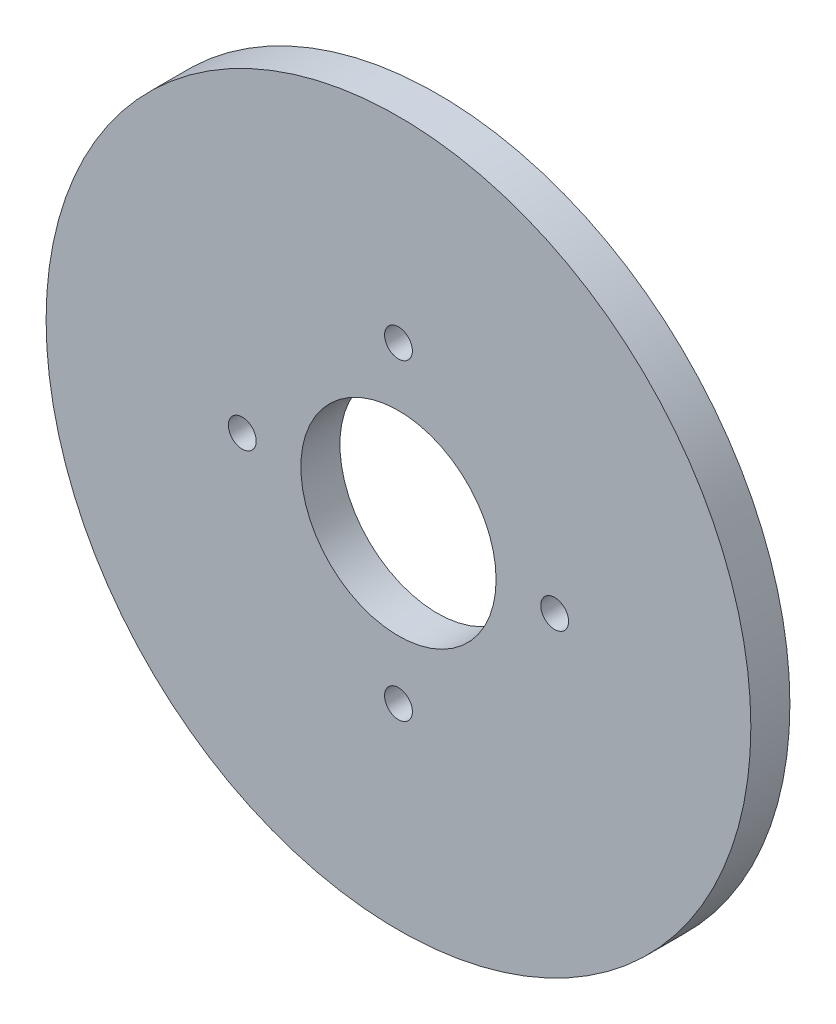
SolidWorks part; units mm, degrees
material "6061 Alloy"
ref_plane "Front Plane" through (0, 0, 0) normal (0, 0, 1) x (1, 0, 0)
ref_plane "Top Plane" through (0, 0, 0) normal (0, 1, 0) x (1, 0, 0)
ref_plane "Right Plane" through (0, 0, 0) normal (1, 0, 0) x (0, 0, -1)
sketch "Sketch1" plane through (0, 0, 0) normal (0, 0, 1) x (1, 0, 0)
  circle A0 centre (0, 0) radius 28.6512
  circle A1 centre (0, 0) radius 7.9375
  dimension "D1" = 57.3024
  dimension "D2" = 15.875
extrude "Boss-Extrude1" add sketch "Sketch1" along normal blind 3.175
hole_wizard "Tap Drill for #4-40 Tap1" positions "Sketch2" profile "Sketch3" hole size "#4-40" standard "ANSI Inch"
sketch "Sketch2" plane through (0, 0, 3.175) normal (0, 0, 1) x (1, 0, 0)
  point P0 (0, 12.7)
  point P2 (0, -12.7)
  point P4 (12.7, 0)
  point P6 (-12.7, 0)
  dimension "D1" = 12.7
  dimension "D2" = 12.7
  dimension "D3" = 12.7
  dimension "D4" = 12.7
sketch "Sketch3" plane through (0, 12.7, 3.175) normal (1, 0, 0) x (0, -1, 0)
  line L0 (0, 0) -> (0, 4.6792)
  line L1 (0, 4.6792) -> (1.1303, 4)
  line L2 (1.1303, 4) -> (1.1303, 0)
  line L5 (1.1303, 0) -> (0, 0)
  line L10 (0, 4.6792) -> (-1.1303, 4) construction
  line L11 (0, -6.35) -> (0, 107.95) construction
  dimension "Hole Dia." = 2.2606
  dimension "Hole Depth" = 4
  dimension "Drill Angle" = 118
